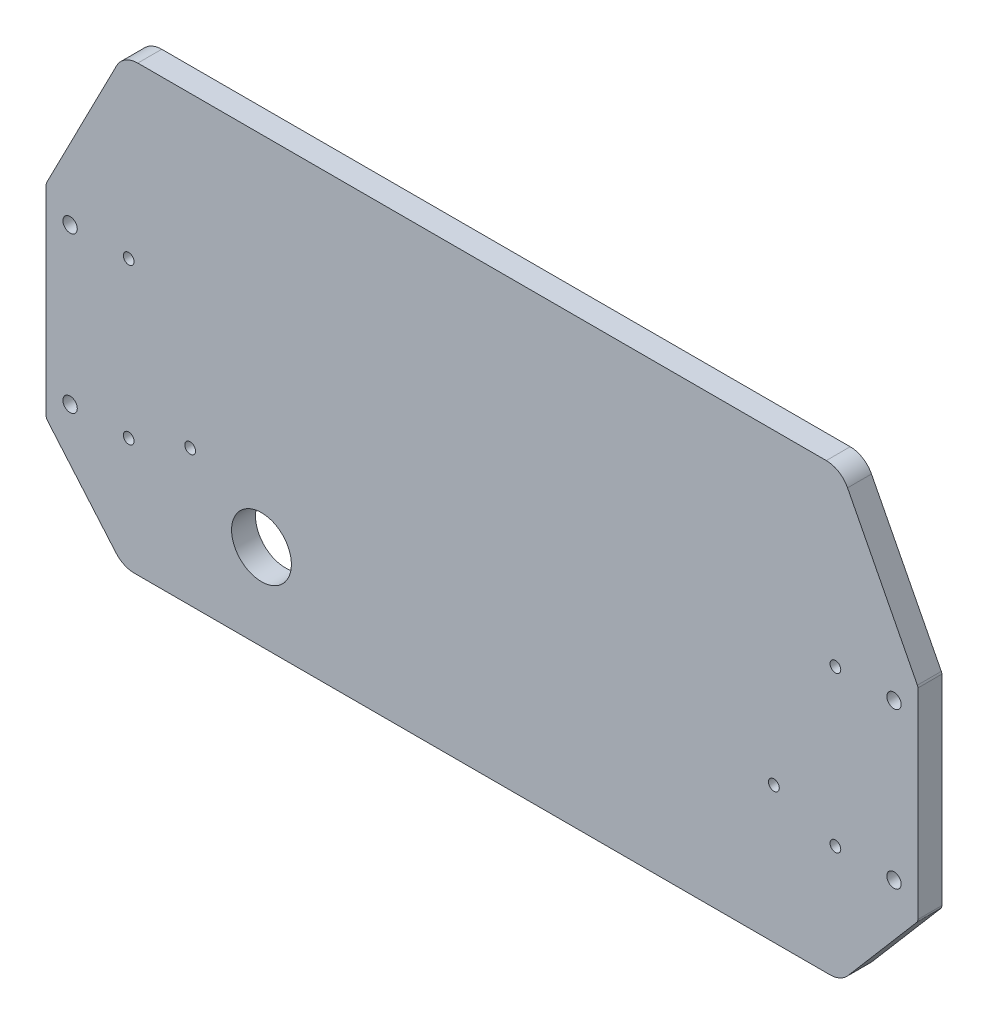
SolidWorks part; units mm, degrees
ref_plane "Plan de face" through (0, 0, 0) normal (0, 0, 1) x (1, 0, 0)
ref_plane "Plan de dessus" through (0, 0, 0) normal (0, 1, 0) x (1, 0, 0)
ref_plane "Plan de droite" through (0, 0, 0) normal (1, 0, 0) x (0, 0, -1)
sketch "Esquisse1" plane through (0, 0, 0) normal (0, 0, 1) x (1, 0, 0)
  line L0 (-182.2, 42.5) -> (-150, 105.2)
  line L1 (-182.2, 42.5) -> (182.2, 42.5)
  line L2 (-182.2, 42.5) -> (-182.2, -42.5)
  line L3 (-182.2, -42.5) -> (182.2, -42.5)
  line L4 (182.2, 42.5) -> (182.2, -42.5)
  line L5 (-150, 105.2) -> (150, 105.2)
  line L6 (-150, 105.2) -> (-150, 42.5)
  line L7 (-150, 42.5) -> (150, 42.5)
  line L8 (150, 105.2) -> (150, 42.5)
  line L9 (-150, -42.5) -> (150, -42.5)
  line L10 (-150, -42.5) -> (-150, -80.2)
  line L11 (-150, -80.2) -> (150, -80.2)
  line L12 (150, -42.5) -> (150, -80.2)
  line L13 (150, 105.2) -> (182.2, 42.5)
  line L14 (182.2, -42.5) -> (150, -80.2)
  line L15 (-150, -80.2) -> (-182.2, -42.5)
  dimension "D1" = 85
  dimension "D2" = 364.4
  dimension "D3" = 300
  dimension "D4" = 300
  dimension "D5" = 32.2
  dimension "D6" = 32.2
  dimension "D7" = 37.7
  dimension "D8" = 62.7
  dimension "D9" = 150
  dimension "D10" = 42.5
extrude "Boss.-Extru.1" add sketch "Esquisse1" along normal blind 10 contours L4 L1 L2 L3 | L8 L5 L6 L1 | L6 L0 L1 | L12 L3 L10 L11 | L15 L10 L3 | L13 L8 L1 | L14 L3 L12
sketch "Esquisse2" plane through (0, 0, 10) normal (0, 0, 1) x (1, 0, 0)
  line L1 (-182.2, 22.5) -> (-162.2, 22.5)
  line L2 (-182.2, 22.5) -> (-182.2, 42.5)
  line L3 (-182.2, 42.5) -> (-162.2, 42.5)
  line L4 (-162.2, 22.5) -> (-162.2, 42.5)
  line L5 (162.2, 22.5) -> (182.2, 22.5)
  line L6 (162.2, 22.5) -> (162.2, 42.5)
  line L7 (162.2, 42.5) -> (182.2, 42.5)
  line L8 (182.2, 22.5) -> (182.2, 42.5)
  line L9 (162.2, -22.5) -> (182.2, -22.5)
  line L10 (162.2, -22.5) -> (162.2, -42.5)
  line L11 (162.2, -42.5) -> (182.2, -42.5)
  line L12 (182.2, -22.5) -> (182.2, -42.5)
  line L13 (-182.2, -22.5) -> (-162.2, -22.5)
  line L14 (-182.2, -22.5) -> (-182.2, -42.5)
  line L15 (-182.2, -42.5) -> (-162.2, -42.5)
  line L16 (-162.2, -22.5) -> (-162.2, -42.5)
  line L17 (182.2, 42.5) -> (182.2, -42.5) construction
  line L18 (-182.2, 42.5) -> (-182.2, -42.5) construction
  dimension "D1" = 20
  dimension "D2" = 20
  dimension "D3" = 20
  dimension "D4" = 20
  dimension "D5" = 20
  dimension "D6" = 20
  dimension "D7" = 20
  dimension "D8" = 20
  dimension "D9" = 20
  dimension "D10" = 20
  dimension "D11" = 20
  dimension "D12" = 20
  dimension "D13" = 0
  dimension "D14" = 0
  dimension "D15" = 0
  dimension "D16" = 0
sketch "Esquisse3" plane through (0, 0, 10) normal (0, 0, 1) x (1, 0, 0)
  line L0 (-182.2, 42.5) -> (-162.2, 42.5) construction
  line L2 (-162.2, 22.5) -> (-162.2, 42.5) construction
  line L4 (-182.2, -22.5) -> (-162.2, -22.5) construction
  line L5 (-162.2, -22.5) -> (-162.2, -42.5) construction
  line L8 (162.2, -22.5) -> (182.2, -22.5) construction
  line L9 (162.2, -22.5) -> (162.2, -42.5) construction
  line L12 (162.2, 22.5) -> (162.2, 42.5) construction
  line L13 (162.2, 42.5) -> (182.2, 42.5) construction
  circle A0 centre (-147.7, 32.5) radius 2.25
  circle A1 centre (-172.2, 32.5) radius 3
  circle A3 centre (-172.2, -32.5) radius 3
  circle A4 centre (-147.7, -32.5) radius 2.25
  circle A6 centre (172.2, -32.5) radius 3
  circle A7 centre (147.7, -32.5) radius 2.25
  circle A9 centre (172.2, 32.5) radius 3
  circle A10 centre (147.7, 32.5) radius 2.25
  dimension "D1" = 6
  dimension "D5" = 4.5
  dimension "D10" = 6
  dimension "D13" = 4.5
  dimension "D14" = 14.5
  dimension "D17" = 14.5
  dimension "D19" = 6
  dimension "D27" = 4.5
  dimension "D28" = 4.5
  dimension "D30" = 6
  dimension "D15" = 14.5
  dimension "D7" = 14.5
  dimension "D2" = 10
  dimension "D3" = 10
  dimension "D4" = 10
  dimension "D11" = 10
  dimension "D12" = 10
  dimension "D16" = 10
  dimension "D20" = 10
  dimension "D21" = 10
  dimension "D26" = 10
  dimension "D31" = 10
  dimension "D32" = 10
  dimension "D33" = 10
extrude "Enlèv. mat.-Extru.1" cut sketch "Esquisse3" against normal blind 10
sketch "Esquisse4" plane through (0, 0, 10) normal (0, 0, 1) x (1, 0, 0)
  line L0 (-182.2, 42.5) -> (-182.2, -42.5) construction
  line L1 (-150, -80.2) -> (150, -80.2) construction
  line L2 (182.2, 42.5) -> (182.2, -42.5) construction
  circle A0 centre (-122, -23.2) radius 2.25
  circle A1 centre (122, -23.2) radius 2.25
  dimension "D1" = 4.5
  dimension "D2" = 4.5
  dimension "D3" = 60.2
  dimension "D4" = 57
  dimension "D5" = 57
  dimension "D6" = 60.2
extrude "Enlèv. mat.-Extru.2" cut sketch "Esquisse4" against normal blind 10
fillet "Congé1" radius 10 4 edges at (-150, 105.2, 5) (150, 105.2, 5) (150, -80.2, 5) (-150, -80.2, 5)
fillet "Congé2" radius 2 4 edges at (-182.2, -42.5, 5) (-182.2, 42.5, 5) (182.2, -42.5, 5) (182.2, 42.5, 5)
sketch "Esquisse5" plane through (0, 0, 0) normal (0, 0, -1) x (-1, 0, 0)
  line L0 (145.39, -80.2) -> (-145.39, -80.2) construction
  line L1 (182.2, 42.0165) -> (182.2, -41.7621) construction
  circle A0 centre (92.2, -44.2) radius 12.5
  dimension "D1" = 25
  dimension "D2" = 36
  dimension "D3" = 90
extrude "Enlèv. mat.-Extru.3" cut sketch "Esquisse5" against normal blind 10
